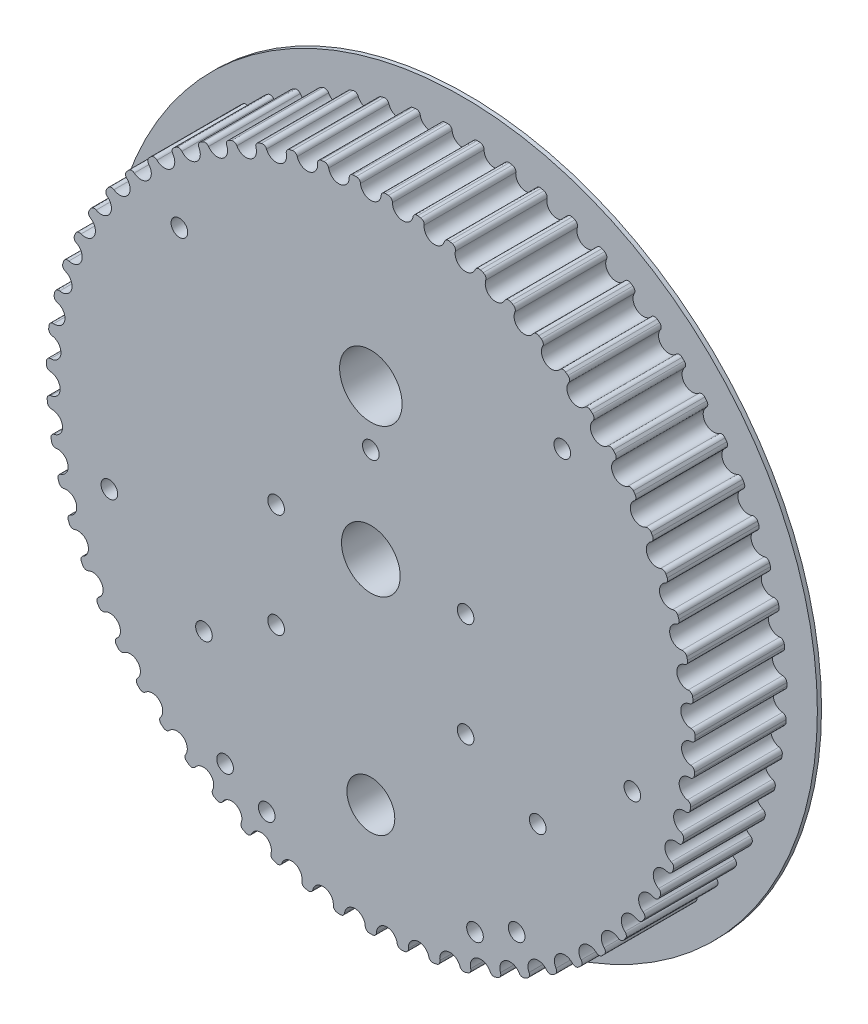
SolidWorks part; units mm, degrees
material "PETG"
ref_plane "Front Plane" through (0, 0, 0) normal (0, 0, 1) x (1, 0, 0)
ref_plane "Top Plane" through (0, 0, 0) normal (0, 1, 0) x (1, 0, 0)
ref_plane "Right Plane" through (0, 0, 0) normal (1, 0, 0) x (0, 0, -1)
sketch "Sketch1" plane through (0, 0, 0) normal (0, 0, 1) x (1, 0, 0)
  line L0 (0, 0) -> (0, 50000) construction
  line L1 (0, 0) -> (3.9983, 80.1144) construction
  line L2 (0, 0) -> (-3.9983, 80.1144) construction
  circle A0 centre (0, 0) radius 80.2141 construction
  arc A1 (-2.4815, 76.9081) -> (2.4815, 76.9081) centre (0, 77.1141) ccw
  arc A2 (3.8832, 77.8073) -> (-3.8832, 77.8073) centre (0, 0) ccw construction
  arc A3 (-2.4815, 76.9081) -> (-3.5233, 77.8244) centre (-3.478, 76.8254) ccw
  arc A4 (3.5233, 77.8244) -> (2.4815, 76.9081) centre (3.478, 76.8254) ccw
  arc A5 (-3.5233, 77.8244) -> (-3.8832, 77.8073) centre (0, 0) ccw
  arc A6 (3.5233, 77.8244) -> (3.8832, 77.8073) centre (0, 0) cw
  arc A7 (4.243, 77.7885) -> (3.8832, 77.8073) centre (0, 0) ccw
  arc A8 (5.1884, 76.773) -> (4.243, 77.7885) centre (4.1886, 76.7899) ccw
  arc A9 (5.1884, 76.773) -> (10.1267, 76.2789) centre (7.6781, 76.7309) ccw
  arc A10 (11.2546, 77.0868) -> (10.1267, 76.2789) centre (11.1101, 76.0973) ccw
  arc A11 (11.2546, 77.0868) -> (11.611, 77.034) centre (0, 0) cw
  arc A12 (11.9672, 76.9794) -> (11.611, 77.034) centre (0, 0) ccw
  arc A13 (12.8068, 75.8749) -> (11.9672, 76.9794) centre (11.8136, 75.9913) ccw
  arc A14 (12.8068, 75.8749) -> (17.6713, 74.8915) centre (15.2799, 75.5851) ccw
  arc A15 (18.874, 75.5832) -> (17.6713, 74.8915) centre (18.6317, 74.613) ccw
  arc A16 (18.874, 75.5832) -> (19.2234, 75.4951) centre (0, 0) cw
  arc A17 (19.5724, 75.4054) -> (19.2234, 75.4951) centre (0, 0) ccw
  arc A18 (20.2978, 74.2227) -> (19.5724, 75.4054) centre (19.3212, 74.4374) ccw
  arc A19 (20.2978, 74.2227) -> (25.0403, 72.7599) centre (22.7298, 73.6881) ccw
  arc A20 (26.3059, 73.3284) -> (25.0403, 72.7599) centre (25.9682, 72.3871) ccw
  arc A21 (26.3059, 73.3284) -> (26.6448, 73.2059) centre (0, 0) cw
  arc A22 (26.9831, 73.0819) -> (26.6448, 73.2059) centre (0, 0) ccw
  arc A23 (27.5872, 71.8329) -> (26.9831, 73.0819) centre (26.6367, 72.1438) ccw
  arc A24 (27.5872, 71.8329) -> (32.1604, 69.9051) centre (29.9538, 71.0588) ccw
  arc A25 (33.4763, 70.3448) -> (32.1604, 69.9051) centre (33.0466, 69.4418) ccw
  arc A26 (33.4763, 70.3448) -> (33.8013, 70.1892) centre (0, 0) cw
  arc A27 (34.1256, 70.0321) -> (33.8013, 70.1892) centre (0, 0) ccw
  arc A28 (34.6023, 68.7291) -> (34.1256, 70.0321) centre (33.6876, 69.1331) ccw
  arc A29 (34.6023, 68.7291) -> (38.9609, 66.3556) centre (36.8801, 67.7233) ccw
  arc A30 (40.314, 66.662) -> (38.9609, 66.3556) centre (39.7965, 65.8063) ccw
  arc A31 (40.314, 66.662) -> (40.6219, 66.4749) centre (0, 0) cw
  arc A32 (40.929, 66.2862) -> (40.6219, 66.4749) centre (0, 0) ccw
  arc A33 (41.2736, 64.9423) -> (40.929, 66.2862) centre (40.4036, 65.4354) ccw
  arc A34 (41.2736, 64.9423) -> (45.3742, 62.1466) centre (43.4399, 63.7147) ccw
  arc A35 (46.7511, 62.3168) -> (45.3742, 62.1466) centre (46.151, 61.5169) ccw
  arc A36 (46.7511, 62.3168) -> (47.0388, 62.0999) centre (0, 0) cw
  arc A37 (47.3256, 61.8816) -> (47.0388, 62.0999) centre (0, 0) ccw
  arc A38 (47.5347, 60.5101) -> (47.3256, 61.8816) centre (46.7181, 61.0873) ccw
  arc A39 (47.5347, 60.5101) -> (51.3365, 57.32) centre (49.568, 59.0728) ccw
  arc A40 (52.7235, 57.3522) -> (51.3365, 57.32) centre (52.0467, 56.616) ccw
  arc A41 (52.7235, 57.3522) -> (52.9882, 57.1077) centre (0, 0) cw
  arc A42 (53.2518, 56.862) -> (52.9882, 57.1077) centre (0, 0) ccw
  arc A43 (53.3233, 55.4765) -> (53.2518, 56.862) centre (52.5683, 56.1321) ccw
  arc A44 (53.3233, 55.4765) -> (56.7886, 51.9237) centre (55.2034, 53.8439) ccw
  arc A45 (58.172, 51.8177) -> (56.7886, 51.9237) centre (57.4253, 51.1525) ccw
  arc A46 (58.172, 51.8177) -> (58.411, 51.548) centre (0, 0) cw
  arc A47 (58.6488, 51.2773) -> (58.411, 51.548) centre (0, 0) ccw
  arc A48 (58.582, 49.8915) -> (58.6488, 51.2773) centre (57.896, 50.6191) ccw
  arc A49 (58.582, 49.8915) -> (61.6764, 46.0113) centre (60.2902, 48.0798) ccw
  arc A50 (63.0423, 45.7681) -> (61.6764, 46.0113) centre (62.233, 45.1806) ccw
  arc A51 (63.0423, 45.7681) -> (63.2533, 45.476) centre (0, 0) cw
  arc A52 (63.463, 45.183) -> (63.2533, 45.476) centre (0, 0) ccw
  arc A53 (63.2585, 43.8107) -> (63.463, 45.183) centre (62.6483, 44.603) ccw
  arc A54 (63.2585, 43.8107) -> (65.9511, 39.6417) centre (64.7778, 41.838) ccw
  arc A55 (67.286, 39.2637) -> (65.9511, 39.6417) centre (66.4223, 38.7597) ccw
  arc A56 (67.286, 39.2637) -> (67.4669, 38.952) centre (0, 0) cw
  arc A57 (67.6464, 38.6396) -> (67.4669, 38.952) centre (0, 0) ccw
  arc A58 (67.3063, 37.2945) -> (67.6464, 38.6396) centre (66.778, 38.1436) ccw
  arc A59 (67.3063, 37.2945) -> (69.5704, 32.8781) centre (68.6217, 35.1803) ccw
  arc A60 (70.8611, 32.3691) -> (69.5704, 32.8781) centre (69.9515, 31.9536) ccw
  arc A61 (70.8611, 32.3691) -> (71.01, 32.0409) centre (0, 0) cw
  arc A62 (71.1575, 31.7122) -> (71.01, 32.0409) centre (0, 0) ccw
  arc A63 (70.6852, 30.4076) -> (71.1575, 31.7122) centre (70.2441, 31.3051) ccw
  arc A64 (70.6852, 30.4076) -> (72.4983, 25.7878) centre (71.7835, 28.1729) ccw
  arc A65 (73.7319, 25.1527) -> (72.4983, 25.7878) centre (72.7854, 24.8299) ccw
  arc A66 (73.7319, 25.1527) -> (73.8474, 24.8114) centre (0, 0) cw
  arc A67 (73.9614, 24.4696) -> (73.8474, 24.8114) centre (0, 0) ccw
  arc A68 (73.3615, 23.2186) -> (73.9614, 24.4696) centre (73.012, 24.1555) ccw
  arc A69 (73.3615, 23.2186) -> (74.7057, 18.4411) centre (74.2319, 20.8856) ccw
  arc A70 (75.8699, 17.6864) -> (74.7057, 18.4411) centre (74.896, 17.4594) ccw
  arc A71 (75.8699, 17.6864) -> (75.9509, 17.3353) centre (0, 0) cw
  arc A72 (76.0302, 16.9838) -> (75.9509, 17.3353) centre (0, 0) ccw
  arc A73 (75.3088, 15.7987) -> (76.0302, 16.9838) centre (75.0543, 16.7658) ccw
  arc A74 (75.3088, 15.7987) -> (76.1706, 10.9112) centre (75.9426, 13.3907) ccw
  arc A75 (77.2539, 10.0443) -> (76.1706, 10.9112) centre (76.2622, 9.9154) ccw
  arc A76 (77.2539, 10.0443) -> (77.2995, 9.6869) centre (0, 0) cw
  arc A77 (77.3435, 9.3292) -> (77.2995, 9.6869) centre (0, 0) ccw
  arc A78 (76.5076, 8.2219) -> (77.3435, 9.3292) centre (76.3507, 9.2095) ccw
  arc A79 (76.5076, 8.2219) -> (76.8785, 3.2728) centre (76.8985, 5.7627) ccw
  arc A80 (77.8701, 2.3024) -> (76.8785, 3.2728) centre (76.8705, 2.2729) ccw
  arc A81 (77.8701, 2.3024) -> (77.8799, 1.9422) centre (0, 0) cw
  arc A82 (77.888, 1.582) -> (77.8799, 1.9422) centre (0, 0) ccw
  arc A83 (76.9461, 0.5633) -> (77.888, 1.582) centre (76.8882, 1.5616) ccw
  arc A84 (76.9461, 0.5633) -> (76.8224, -4.3981) centre (77.0901, -1.9225) ccw
  arc A85 (77.7124, -5.4624) -> (76.8224, -4.3981) centre (76.7148, -5.3923) ccw
  arc A86 (77.7124, -5.4624) -> (77.6863, -5.8218) centre (0, 0) cw
  arc A87 (77.6585, -6.181) -> (77.6863, -5.8218) centre (0, 0) ccw
  arc A88 (76.6198, -7.1008) -> (77.6585, -6.181) centre (76.6616, -6.1017) ccw
  arc A89 (76.6198, -7.1008) -> (76.0027, -12.0252) centre (76.5156, -9.5887) ccw
  arc A90 (76.7823, -13.1729) -> (76.0027, -12.0252) centre (75.7967, -13.0038) ccw
  arc A91 (76.7823, -13.1729) -> (76.7206, -13.5279) centre (0, 0) cw
  arc A92 (76.6572, -13.8826) -> (76.7206, -13.5279) centre (0, 0) ccw
  arc A93 (75.5321, -14.6944) -> (76.6572, -13.8826) centre (75.6732, -13.7044) ccw
  arc A94 (75.5321, -14.6944) -> (74.4277, -19.5329) centre (75.1807, -17.1595) ccw
  arc A95 (75.0892, -20.7525) -> (74.4277, -19.5329) centre (74.1253, -20.4861) ccw
  arc A96 (75.0892, -20.7525) -> (74.9924, -21.0996) centre (0, 0) cw
  arc A97 (74.894, -21.4462) -> (74.9924, -21.0996) centre (0, 0) ccw
  arc A98 (73.6936, -22.142) -> (74.894, -21.4462) centre (73.9326, -21.1709) ccw
  arc A99 (73.6936, -22.142) -> (72.113, -26.8465) centre (73.0986, -24.5598) ccw
  arc A100 (72.6497, -28.1258) -> (72.113, -26.8465) centre (71.7172, -27.7648) ccw
  arc A101 (72.6497, -28.1258) -> (72.5189, -28.4616) centre (0, 0) cw
  arc A102 (72.3865, -28.7967) -> (72.5189, -28.4616) centre (0, 0) ccw
  arc A103 (71.1228, -29.3694) -> (72.3865, -28.7967) centre (71.4573, -28.427) ccw
  arc A104 (71.1228, -29.3694) -> (69.0816, -33.8932) centre (70.2899, -31.716) ccw
  arc A105 (69.4883, -35.2196) -> (69.0816, -33.8932) centre (68.5963, -34.7676) ccw
  arc A106 (69.4883, -35.2196) -> (69.3247, -35.5407) centre (0, 0) cw
  arc A107 (69.1595, -35.861) -> (69.3247, -35.5407) centre (0, 0) ccw
  arc A108 (67.8451, -36.305) -> (69.1595, -35.861) centre (68.2718, -35.4006) ccw
  arc A109 (67.8451, -36.305) -> (65.3637, -40.6031) centre (66.7828, -38.557) ccw
  arc A110 (65.6363, -41.9634) -> (65.3637, -40.6031) centre (64.7937, -41.4248) ccw
  arc A111 (65.6363, -41.9634) -> (65.4415, -42.2666) centre (0, 0) cw
  arc A112 (65.2453, -42.5688) -> (65.4415, -42.2666) centre (0, 0) ccw
  arc A113 (63.8932, -42.8798) -> (65.2453, -42.5688) centre (64.4077, -42.0224) ccw
  arc A114 (63.8932, -42.8798) -> (60.9961, -46.9094) centre (62.6119, -45.0149) ccw
  arc A115 (61.1319, -48.2902) -> (60.9961, -46.9094) centre (60.3472, -47.6703) ccw
  arc A116 (61.1319, -48.2902) -> (60.9079, -48.5724) centre (0, 0) cw
  arc A117 (60.6826, -48.8536) -> (60.9079, -48.5724) centre (0, 0) ccw
  arc A118 (59.3062, -49.0285) -> (60.6826, -48.8536) centre (59.9036, -48.2265) ccw
  arc A119 (59.3062, -49.0285) -> (56.0223, -52.7496) centre (57.8187, -51.0253) ccw
  arc A120 (56.02, -54.137) -> (56.0223, -52.7496) centre (55.3009, -53.442) ccw
  arc A121 (56.02, -54.137) -> (55.769, -54.3955) centre (0, 0) cw
  arc A122 (55.5168, -54.6529) -> (55.769, -54.3955) centre (0, 0) ccw
  arc A123 (54.1299, -54.6898) -> (55.5168, -54.6529) centre (54.8041, -53.9513) ccw
  arc A124 (54.1299, -54.6898) -> (50.4918, -58.0655) centre (52.4509, -56.5286) ccw
  arc A125 (50.3513, -59.4457) -> (50.4918, -58.0655) centre (49.705, -58.6827) ccw
  arc A126 (50.3513, -59.4457) -> (50.0758, -59.678) centre (0, 0) cw
  arc A127 (49.7992, -59.909) -> (50.0758, -59.678) centre (0, 0) ccw
  arc A128 (48.4155, -59.8076) -> (49.7992, -59.909) centre (49.16, -59.14) ccw
  arc A129 (48.4155, -59.8076) -> (44.4594, -62.8043) centre (46.5618, -61.4701) ccw
  arc A130 (44.1822, -64.1637) -> (44.4594, -62.8043) centre (43.6151, -63.3401) ccw
  arc A131 (44.1822, -64.1637) -> (43.8849, -64.3674) centre (0, 0) cw
  arc A132 (43.5867, -64.5697) -> (43.8849, -64.3674) centre (0, 0) ccw
  arc A133 (42.22, -64.3311) -> (43.5867, -64.5697) centre (43.0272, -63.7408) ccw
  arc A134 (42.22, -64.3311) -> (37.9852, -66.9189) centre (40.21, -65.8008) ccw
  arc A135 (37.574, -68.244) -> (37.9852, -66.9189) centre (37.0917, -67.368) ccw
  arc A136 (37.574, -68.244) -> (37.2579, -68.4171) centre (0, 0) cw
  arc A137 (36.9411, -68.5887) -> (37.2579, -68.4171) centre (0, 0) ccw
  arc A138 (35.6049, -68.2152) -> (36.9411, -68.5887) centre (36.4669, -67.7082) ccw
  arc A139 (35.6049, -68.2152) -> (31.1335, -70.3685) centre (33.4586, -69.4774) ccw
  arc A140 (30.5924, -71.646) -> (31.1335, -70.3685) centre (30.1997, -70.7264) ccw
  arc A141 (30.5924, -71.646) -> (30.2607, -71.7868) centre (0, 0) cw
  arc A142 (29.9283, -71.926) -> (30.2607, -71.7868) centre (0, 0) ccw
  arc A143 (28.6359, -71.4213) -> (29.9283, -71.926) centre (29.5441, -71.0027) ccw
  arc A144 (28.6359, -71.4213) -> (23.9723, -73.1187) centre (26.3746, -72.4635) ccw
  arc A145 (23.3067, -74.336) -> (23.9723, -73.1187) centre (23.0075, -73.3818) ccw
  arc A146 (23.3067, -74.336) -> (22.9626, -74.443) centre (0, 0) cw
  arc A147 (22.6181, -74.5484) -> (22.9626, -74.443) centre (0, 0) ccw
  arc A148 (21.3824, -73.9176) -> (22.6181, -74.5484) centre (22.3277, -73.5915) ccw
  arc A149 (21.3824, -73.9176) -> (16.5729, -75.1422) centre (19.0285, -74.7295) ccw
  arc A150 (15.7894, -76.2872) -> (16.5729, -75.1422) centre (15.5867, -75.308) ccw
  arc A151 (15.7894, -76.2872) -> (15.4364, -76.3594) centre (0, 0) cw
  arc A152 (15.083, -76.43) -> (15.4364, -76.3594) centre (0, 0) ccw
  arc A153 (13.9163, -75.6793) -> (15.083, -76.43) centre (14.8894, -75.449) ccw
  arc A154 (13.9163, -75.6793) -> (9.0088, -76.419) centre (11.4933, -76.2528) ccw
  arc A155 (8.1152, -77.4803) -> (9.0088, -76.419) centre (8.011, -76.4857) ccw
  arc A156 (8.1152, -77.4803) -> (7.7567, -77.517) centre (0, 0) cw
  arc A157 (7.3981, -77.552) -> (7.7567, -77.517) centre (0, 0) ccw
  arc A158 (6.3119, -76.6888) -> (7.3981, -77.552) centre (7.3031, -76.5565) ccw
  arc A159 (6.3119, -76.6888) -> (1.3552, -76.9362) centre (3.8438, -77.0182) ccw
  arc A160 (0.3603, -77.9033) -> (1.3552, -76.9362) centre (0.3557, -76.9033) ccw
  arc A161 (0.3603, -77.9033) -> (0, -77.9041) centre (0, 0) cw
  arc A162 (-0.3603, -77.9033) -> (0, -77.9041) centre (0, 0) ccw
  arc A163 (-1.3552, -76.9362) -> (-0.3603, -77.9033) centre (-0.3557, -76.9033) ccw
  arc A164 (-1.3552, -76.9362) -> (-6.3119, -76.6888) centre (-3.8438, -77.0182) ccw
  arc A165 (-7.3981, -77.552) -> (-6.3119, -76.6888) centre (-7.3031, -76.5565) ccw
  arc A166 (-7.3981, -77.552) -> (-7.7567, -77.517) centre (0, 0) cw
  arc A167 (-8.1152, -77.4803) -> (-7.7567, -77.517) centre (0, 0) ccw
  arc A168 (-9.0088, -76.419) -> (-8.1152, -77.4803) centre (-8.011, -76.4857) ccw
  arc A169 (-9.0088, -76.419) -> (-13.9163, -75.6793) centre (-11.4933, -76.2528) ccw
  arc A170 (-15.083, -76.43) -> (-13.9163, -75.6793) centre (-14.8894, -75.449) ccw
  arc A171 (-15.083, -76.43) -> (-15.4364, -76.3594) centre (0, 0) cw
  arc A172 (-15.7894, -76.2872) -> (-15.4364, -76.3594) centre (0, 0) ccw
  arc A173 (-16.5729, -75.1422) -> (-15.7894, -76.2872) centre (-15.5867, -75.308) ccw
  arc A174 (-16.5729, -75.1422) -> (-21.3824, -73.9176) centre (-19.0285, -74.7295) ccw
  arc A175 (-22.6181, -74.5484) -> (-21.3824, -73.9176) centre (-22.3277, -73.5915) ccw
  arc A176 (-22.6181, -74.5484) -> (-22.9626, -74.443) centre (0, 0) cw
  arc A177 (-23.3067, -74.336) -> (-22.9626, -74.443) centre (0, 0) ccw
  arc A178 (-23.9723, -73.1187) -> (-23.3067, -74.336) centre (-23.0075, -73.3818) ccw
  arc A179 (-23.9723, -73.1187) -> (-28.6359, -71.4213) centre (-26.3746, -72.4635) ccw
  arc A180 (-29.9283, -71.926) -> (-28.6359, -71.4213) centre (-29.5441, -71.0027) ccw
  arc A181 (-29.9283, -71.926) -> (-30.2607, -71.7868) centre (0, 0) cw
  arc A182 (-30.5924, -71.646) -> (-30.2607, -71.7868) centre (0, 0) ccw
  arc A183 (-31.1335, -70.3685) -> (-30.5924, -71.646) centre (-30.1997, -70.7264) ccw
  arc A184 (-31.1335, -70.3685) -> (-35.6049, -68.2152) centre (-33.4586, -69.4774) ccw
  arc A185 (-36.9411, -68.5887) -> (-35.6049, -68.2152) centre (-36.4669, -67.7082) ccw
  arc A186 (-36.9411, -68.5887) -> (-37.2579, -68.4171) centre (0, 0) cw
  arc A187 (-37.574, -68.244) -> (-37.2579, -68.4171) centre (0, 0) ccw
  arc A188 (-37.9852, -66.9189) -> (-37.574, -68.244) centre (-37.0917, -67.368) ccw
  arc A189 (-37.9852, -66.9189) -> (-42.22, -64.3311) centre (-40.21, -65.8008) ccw
  arc A190 (-43.5867, -64.5697) -> (-42.22, -64.3311) centre (-43.0272, -63.7408) ccw
  arc A191 (-43.5867, -64.5697) -> (-43.8849, -64.3674) centre (0, 0) cw
  arc A192 (-44.1822, -64.1637) -> (-43.8849, -64.3674) centre (0, 0) ccw
  arc A193 (-44.4594, -62.8043) -> (-44.1822, -64.1637) centre (-43.6151, -63.3401) ccw
  arc A194 (-44.4594, -62.8043) -> (-48.4155, -59.8076) centre (-46.5618, -61.4701) ccw
  arc A195 (-49.7992, -59.909) -> (-48.4155, -59.8076) centre (-49.16, -59.14) ccw
  arc A196 (-49.7992, -59.909) -> (-50.0758, -59.678) centre (0, 0) cw
  arc A197 (-50.3513, -59.4457) -> (-50.0758, -59.678) centre (0, 0) ccw
  arc A198 (-50.4918, -58.0655) -> (-50.3513, -59.4457) centre (-49.705, -58.6827) ccw
  arc A199 (-50.4918, -58.0655) -> (-54.1299, -54.6898) centre (-52.4509, -56.5286) ccw
  arc A200 (-55.5168, -54.6529) -> (-54.1299, -54.6898) centre (-54.8041, -53.9513) ccw
  arc A201 (-55.5168, -54.6529) -> (-55.769, -54.3955) centre (0, 0) cw
  arc A202 (-56.02, -54.137) -> (-55.769, -54.3955) centre (0, 0) ccw
  arc A203 (-56.0223, -52.7496) -> (-56.02, -54.137) centre (-55.3009, -53.442) ccw
  arc A204 (-56.0223, -52.7496) -> (-59.3062, -49.0285) centre (-57.8187, -51.0253) ccw
  arc A205 (-60.6826, -48.8536) -> (-59.3062, -49.0285) centre (-59.9036, -48.2265) ccw
  arc A206 (-60.6826, -48.8536) -> (-60.9079, -48.5724) centre (0, 0) cw
  arc A207 (-61.1319, -48.2902) -> (-60.9079, -48.5724) centre (0, 0) ccw
  arc A208 (-60.9961, -46.9094) -> (-61.1319, -48.2902) centre (-60.3472, -47.6703) ccw
  arc A209 (-60.9961, -46.9094) -> (-63.8932, -42.8798) centre (-62.6119, -45.0149) ccw
  arc A210 (-65.2453, -42.5688) -> (-63.8932, -42.8798) centre (-64.4077, -42.0224) ccw
  arc A211 (-65.2453, -42.5688) -> (-65.4415, -42.2666) centre (0, 0) cw
  arc A212 (-65.6363, -41.9634) -> (-65.4415, -42.2666) centre (0, 0) ccw
  arc A213 (-65.3637, -40.6031) -> (-65.6363, -41.9634) centre (-64.7937, -41.4248) ccw
  arc A214 (-65.3637, -40.6031) -> (-67.8451, -36.305) centre (-66.7828, -38.557) ccw
  arc A215 (-69.1595, -35.861) -> (-67.8451, -36.305) centre (-68.2718, -35.4006) ccw
  arc A216 (-69.1595, -35.861) -> (-69.3247, -35.5407) centre (0, 0) cw
  arc A217 (-69.4883, -35.2196) -> (-69.3247, -35.5407) centre (0, 0) ccw
  arc A218 (-69.0816, -33.8932) -> (-69.4883, -35.2196) centre (-68.5963, -34.7676) ccw
  arc A219 (-69.0816, -33.8932) -> (-71.1228, -29.3694) centre (-70.2899, -31.716) ccw
  arc A220 (-72.3865, -28.7967) -> (-71.1228, -29.3694) centre (-71.4573, -28.427) ccw
  arc A221 (-72.3865, -28.7967) -> (-72.5189, -28.4616) centre (0, 0) cw
  arc A222 (-72.6497, -28.1258) -> (-72.5189, -28.4616) centre (0, 0) ccw
  arc A223 (-72.113, -26.8465) -> (-72.6497, -28.1258) centre (-71.7172, -27.7648) ccw
  arc A224 (-72.113, -26.8465) -> (-73.6936, -22.142) centre (-73.0986, -24.5598) ccw
  arc A225 (-74.894, -21.4462) -> (-73.6936, -22.142) centre (-73.9326, -21.1709) ccw
  arc A226 (-74.894, -21.4462) -> (-74.9924, -21.0996) centre (0, 0) cw
  arc A227 (-75.0892, -20.7525) -> (-74.9924, -21.0996) centre (0, 0) ccw
  arc A228 (-74.4277, -19.5329) -> (-75.0892, -20.7525) centre (-74.1253, -20.4861) ccw
  arc A229 (-74.4277, -19.5329) -> (-75.5321, -14.6944) centre (-75.1807, -17.1595) ccw
  arc A230 (-76.6572, -13.8826) -> (-75.5321, -14.6944) centre (-75.6732, -13.7044) ccw
  arc A231 (-76.6572, -13.8826) -> (-76.7206, -13.5279) centre (0, 0) cw
  arc A232 (-76.7823, -13.1729) -> (-76.7206, -13.5279) centre (0, 0) ccw
  arc A233 (-76.0027, -12.0252) -> (-76.7823, -13.1729) centre (-75.7967, -13.0038) ccw
  arc A234 (-76.0027, -12.0252) -> (-76.6198, -7.1008) centre (-76.5156, -9.5887) ccw
  arc A235 (-77.6585, -6.181) -> (-76.6198, -7.1008) centre (-76.6616, -6.1017) ccw
  arc A236 (-77.6585, -6.181) -> (-77.6863, -5.8218) centre (0, 0) cw
  arc A237 (-77.7124, -5.4624) -> (-77.6863, -5.8218) centre (0, 0) ccw
  arc A238 (-76.8224, -4.3981) -> (-77.7124, -5.4624) centre (-76.7148, -5.3923) ccw
  arc A239 (-76.8224, -4.3981) -> (-76.9461, 0.5633) centre (-77.0901, -1.9225) ccw
  arc A240 (-77.888, 1.582) -> (-76.9461, 0.5633) centre (-76.8882, 1.5616) ccw
  arc A241 (-77.888, 1.582) -> (-77.8799, 1.9422) centre (0, 0) cw
  arc A242 (-77.8701, 2.3024) -> (-77.8799, 1.9422) centre (0, 0) ccw
  arc A243 (-76.8785, 3.2728) -> (-77.8701, 2.3024) centre (-76.8705, 2.2729) ccw
  arc A244 (-76.8785, 3.2728) -> (-76.5076, 8.2219) centre (-76.8985, 5.7627) ccw
  arc A245 (-77.3435, 9.3292) -> (-76.5076, 8.2219) centre (-76.3507, 9.2095) ccw
  arc A246 (-77.3435, 9.3292) -> (-77.2995, 9.6869) centre (0, 0) cw
  arc A247 (-77.2539, 10.0443) -> (-77.2995, 9.6869) centre (0, 0) ccw
  arc A248 (-76.1706, 10.9112) -> (-77.2539, 10.0443) centre (-76.2622, 9.9154) ccw
  arc A249 (-76.1706, 10.9112) -> (-75.3088, 15.7987) centre (-75.9426, 13.3907) ccw
  arc A250 (-76.0302, 16.9838) -> (-75.3088, 15.7987) centre (-75.0543, 16.7658) ccw
  arc A251 (-76.0302, 16.9838) -> (-75.9509, 17.3353) centre (0, 0) cw
  arc A252 (-75.8699, 17.6864) -> (-75.9509, 17.3353) centre (0, 0) ccw
  arc A253 (-74.7057, 18.4411) -> (-75.8699, 17.6864) centre (-74.896, 17.4594) ccw
  arc A254 (-74.7057, 18.4411) -> (-73.3615, 23.2186) centre (-74.2319, 20.8856) ccw
  arc A255 (-73.9614, 24.4696) -> (-73.3615, 23.2186) centre (-73.012, 24.1555) ccw
  arc A256 (-73.9614, 24.4696) -> (-73.8474, 24.8114) centre (0, 0) cw
  arc A257 (-73.7319, 25.1527) -> (-73.8474, 24.8114) centre (0, 0) ccw
  arc A258 (-72.4983, 25.7878) -> (-73.7319, 25.1527) centre (-72.7854, 24.8299) ccw
  arc A259 (-72.4983, 25.7878) -> (-70.6852, 30.4076) centre (-71.7835, 28.1729) ccw
  arc A260 (-71.1575, 31.7122) -> (-70.6852, 30.4076) centre (-70.2441, 31.3051) ccw
  arc A261 (-71.1575, 31.7122) -> (-71.01, 32.0409) centre (0, 0) cw
  arc A262 (-70.8611, 32.3691) -> (-71.01, 32.0409) centre (0, 0) ccw
  arc A263 (-69.5704, 32.8781) -> (-70.8611, 32.3691) centre (-69.9515, 31.9536) ccw
  arc A264 (-69.5704, 32.8781) -> (-67.3063, 37.2945) centre (-68.6217, 35.1803) ccw
  arc A265 (-67.6464, 38.6396) -> (-67.3063, 37.2945) centre (-66.778, 38.1436) ccw
  arc A266 (-67.6464, 38.6396) -> (-67.4669, 38.952) centre (0, 0) cw
  arc A267 (-67.286, 39.2637) -> (-67.4669, 38.952) centre (0, 0) ccw
  arc A268 (-65.9511, 39.6417) -> (-67.286, 39.2637) centre (-66.4223, 38.7597) ccw
  arc A269 (-65.9511, 39.6417) -> (-63.2585, 43.8107) centre (-64.7778, 41.838) ccw
  arc A270 (-63.463, 45.183) -> (-63.2585, 43.8107) centre (-62.6483, 44.603) ccw
  arc A271 (-63.463, 45.183) -> (-63.2533, 45.476) centre (0, 0) cw
  arc A272 (-63.0423, 45.7681) -> (-63.2533, 45.476) centre (0, 0) ccw
  arc A273 (-61.6764, 46.0113) -> (-63.0423, 45.7681) centre (-62.233, 45.1806) ccw
  arc A274 (-61.6764, 46.0113) -> (-58.582, 49.8915) centre (-60.2902, 48.0798) ccw
  arc A275 (-58.6488, 51.2773) -> (-58.582, 49.8915) centre (-57.896, 50.6191) ccw
  arc A276 (-58.6488, 51.2773) -> (-58.411, 51.548) centre (0, 0) cw
  arc A277 (-58.172, 51.8177) -> (-58.411, 51.548) centre (0, 0) ccw
  arc A278 (-56.7886, 51.9237) -> (-58.172, 51.8177) centre (-57.4253, 51.1525) ccw
  arc A279 (-56.7886, 51.9237) -> (-53.3233, 55.4765) centre (-55.2034, 53.8439) ccw
  arc A280 (-53.2518, 56.862) -> (-53.3233, 55.4765) centre (-52.5683, 56.1321) ccw
  arc A281 (-53.2518, 56.862) -> (-52.9882, 57.1077) centre (0, 0) cw
  arc A282 (-52.7235, 57.3522) -> (-52.9882, 57.1077) centre (0, 0) ccw
  arc A283 (-51.3365, 57.32) -> (-52.7235, 57.3522) centre (-52.0467, 56.616) ccw
  arc A284 (-51.3365, 57.32) -> (-47.5347, 60.5101) centre (-49.568, 59.0728) ccw
  arc A285 (-47.3256, 61.8816) -> (-47.5347, 60.5101) centre (-46.7181, 61.0873) ccw
  arc A286 (-47.3256, 61.8816) -> (-47.0388, 62.0999) centre (0, 0) cw
  arc A287 (-46.7511, 62.3168) -> (-47.0388, 62.0999) centre (0, 0) ccw
  arc A288 (-45.3742, 62.1466) -> (-46.7511, 62.3168) centre (-46.151, 61.5169) ccw
  arc A289 (-45.3742, 62.1466) -> (-41.2736, 64.9423) centre (-43.4399, 63.7147) ccw
  arc A290 (-40.929, 66.2862) -> (-41.2736, 64.9423) centre (-40.4036, 65.4354) ccw
  arc A291 (-40.929, 66.2862) -> (-40.6219, 66.4749) centre (0, 0) cw
  arc A292 (-40.314, 66.662) -> (-40.6219, 66.4749) centre (0, 0) ccw
  arc A293 (-38.9609, 66.3556) -> (-40.314, 66.662) centre (-39.7965, 65.8063) ccw
  arc A294 (-38.9609, 66.3556) -> (-34.6023, 68.7291) centre (-36.8801, 67.7233) ccw
  arc A295 (-34.1256, 70.0321) -> (-34.6023, 68.7291) centre (-33.6876, 69.1331) ccw
  arc A296 (-34.1256, 70.0321) -> (-33.8013, 70.1892) centre (0, 0) cw
  arc A297 (-33.4763, 70.3448) -> (-33.8013, 70.1892) centre (0, 0) ccw
  arc A298 (-32.1604, 69.9051) -> (-33.4763, 70.3448) centre (-33.0466, 69.4418) ccw
  arc A299 (-32.1604, 69.9051) -> (-27.5872, 71.8329) centre (-29.9538, 71.0588) ccw
  arc A300 (-26.9831, 73.0819) -> (-27.5872, 71.8329) centre (-26.6367, 72.1438) ccw
  arc A301 (-26.9831, 73.0819) -> (-26.6448, 73.2059) centre (0, 0) cw
  arc A302 (-26.3059, 73.3284) -> (-26.6448, 73.2059) centre (0, 0) ccw
  arc A303 (-25.0403, 72.7599) -> (-26.3059, 73.3284) centre (-25.9682, 72.3871) ccw
  arc A304 (-25.0403, 72.7599) -> (-20.2978, 74.2227) centre (-22.7298, 73.6881) ccw
  arc A305 (-19.5724, 75.4054) -> (-20.2978, 74.2227) centre (-19.3212, 74.4374) ccw
  arc A306 (-19.5724, 75.4054) -> (-19.2234, 75.4951) centre (0, 0) cw
  arc A307 (-18.874, 75.5832) -> (-19.2234, 75.4951) centre (0, 0) ccw
  arc A308 (-17.6713, 74.8915) -> (-18.874, 75.5832) centre (-18.6317, 74.613) ccw
  arc A309 (-17.6713, 74.8915) -> (-12.8068, 75.8749) centre (-15.2799, 75.5851) ccw
  arc A310 (-11.9672, 76.9794) -> (-12.8068, 75.8749) centre (-11.8136, 75.9913) ccw
  arc A311 (-11.9672, 76.9794) -> (-11.611, 77.034) centre (0, 0) cw
  arc A312 (-11.2546, 77.0868) -> (-11.611, 77.034) centre (0, 0) ccw
  arc A313 (-10.1267, 76.2789) -> (-11.2546, 77.0868) centre (-11.1101, 76.0973) ccw
  arc A314 (-10.1267, 76.2789) -> (-5.1884, 76.773) centre (-7.6781, 76.7309) ccw
  arc A315 (-4.243, 77.7885) -> (-5.1884, 76.773) centre (-4.1886, 76.7899) ccw
  arc A316 (-4.243, 77.7885) -> (-3.8832, 77.8073) centre (0, 0) cw
  point P9 (0, 74.6241)
  point P11 (0, 80.2141)
  point P12 (0, 77.9041)
  dimension "D1" = 160.4282
  dimension "D6" = 1
  dimension "D3" = 2.49
  dimension "D4" = 5.59
  dimension "D5" = 3.28
  dimension "D2" = 8
  dimension "D7" = 63
extrude "Boss-Extrude1" add sketch "Sketch1" along normal blind 22 contours A316 A315 A314 A313 A312 A311 A310 A309 A308 A307 A306 A305 A304 A303 A302 A301 A300 A299 A298 A297 A296 A295 A294 A293 A292 A291 A290 A289 A288 A287 A286 A285 A284 A283 A282 A281 A280 A279 A278 A277 A276 A275 A274 A273 A272 A271 A270 A269 A268 A267 A266
sketch "Sketch2" plane through (0, 0, 0) normal (0, 0, -1) x (-1, 0, 0)
  circle A0 centre (0, 0) radius 85.2141
  dimension "D1" = 170.4282
extrude "Boss-Extrude2" add sketch "Sketch2" along normal blind 1
sketch "Sketch3" plane through (0, 0, 22) normal (0, 0, 1) x (1, 0, 0)
  circle A0 centre (0, 0) radius 7.05
  circle A1 centre (0, -51.05) radius 5.75
  circle A2 centre (0, 36) radius 7.5
  dimension "D1" = 14.1
  dimension "D2" = 15
  dimension "D4" = 11.5
  dimension "D3" = 36
  dimension "D5" = 51.05
extrude "Cut-Extrude1" cut sketch "Sketch3" against normal through all
sketch "Sketch4" plane through (0, 0, 22) normal (0, 0, 1) x (1, 0, 0)
  line L0 (0, 0) -> (0, 50000) construction
  line L1 (0, 0) -> (-45.9619, 45.9619) construction
  line L2 (0, 0) -> (45.9619, 45.9619) construction
  line L3 (0, 0) -> (-62.7852, -16.8232) construction
  line L4 (0, 0) -> (62.7852, -16.8232) construction
  line L5 (-22.75, -25) -> (-40.0705, -35) construction
  line L6 (22.75, -25) -> (40.0705, -35) construction
  circle A0 centre (-45.9619, 45.9619) radius 2
  circle A1 centre (45.9619, 45.9619) radius 2
  circle A2 centre (-25, -65) radius 2
  circle A3 centre (25, -65) radius 2
  circle A4 centre (-62.7852, -16.8232) radius 2
  circle A5 centre (62.7852, -16.8232) radius 2
  circle A6 centre (-35, -60) radius 2
  circle A7 centre (35, -60) radius 2
  circle A8 centre (-22.75, 0) radius 2
  circle A9 centre (22.75, 0) radius 2
  circle A10 centre (0, 22.75) radius 2
  circle A11 centre (-22.75, -25) radius 2
  circle A12 centre (22.75, -25) radius 2
  circle A13 centre (-40.0705, -35) radius 2
  circle A14 centre (40.0705, -35) radius 2
  point P34 (0, 0)
  dimension "D1" = 4
  dimension "D2" = 65
  dimension "D3" = 45
  dimension "D4" = 25
  dimension "D5" = 65
  dimension "D6" = 25
  dimension "D7" = 60
  dimension "D8" = 35
  dimension "D9" = 60
  dimension "D10" = 35
  dimension "D11" = 22.75
  dimension "D12" = 22.75
  dimension "D13" = 22.75
  dimension "D14" = 25
  dimension "D15" = 60
  dimension "D16" = 20
extrude "Cut-Extrude2" cut sketch "Sketch4" against normal blind 18
equation "\"tol_dia_id_intfc\" = 0.0500mm ' For hole diameters - Interference fit"
equation "\"tol_dia_id_slip\"  = 0.0750mm ' For hole diameters - Slip fit"
equation "\"tol_dia_id_clear\" = 0.1000mm ' For hole diameters - Clearance fit"
equation "\"tol_dia_od_intfc\" = 0.0500mm ' For shaft diameters - Interference fit"
equation "\"tol_dia_od_slip\"  = 0.0750mm ' For shaft diameters - Slip fit"
equation "\"tol_dia_od_clear\" = 0.1000mm ' For shaft diameters - Clearance fit"
equation "\"tol_general_intfc\"= 0.0250mm ' For general parts (Horiz) - Interference fit"
equation "\"tol_general_slip\" = 0.0375mm ' For general parts (Horiz) - Slip fit"
equation "\"tol_general_clear\"= 0.0500mm ' For general parts (Horiz) - Clearance fit"
equation "\"tol_layer_intfc\"  = 0.0250mm ' For all parts (Vert) - Interference fit"
equation "\"tol_layer_slip\"   = 0.0375mm ' For all parts (Vert) - Slip fit"
equation "\"tol_layer_clear\"  = 0.0500mm ' For all parts (Vert) - Clearance fit"
equation "\"tol_corner_rad\"   = 0.100mm ' For corners that fit into other parts"
equation "\"pitch\"= 8mm"
equation "\"n\"= 63"
equation "\"pitch_dia\"= \"pitch\" * \"n\" / PI"
equation "\"belt_width\"= 22mm"
equation "\"D1@Sketch1\"=\"pitch_dia\""
equation "\"D2@Sketch1\"=\"pitch\""
equation "\"D7@Sketch1\"=\"n\""
equation "\"D1@Extrude-Thin2\"=\"belt_width\""
equation "\"D1@Boss-Extrude1\"=\"belt_width\""
equation "\"D1@Sketch2\"=\"pitch_dia\"+10"
equation "\"D1@Sketch3\"=14.00mm + \"tol_dia_id_clear\""
equation "\"D1@Sketch4\"=3.95+\"tol_dia_id_intfc\""
equation "\"D6@Sketch4\"=\"D4@Sketch4\""
equation "\"D10@Sketch4\"=\"D8@Sketch4\""
equation "\"D12@Sketch4\"=\"D11@Sketch4\""
equation "\"D13@Sketch4\"=\"D11@Sketch4\""
